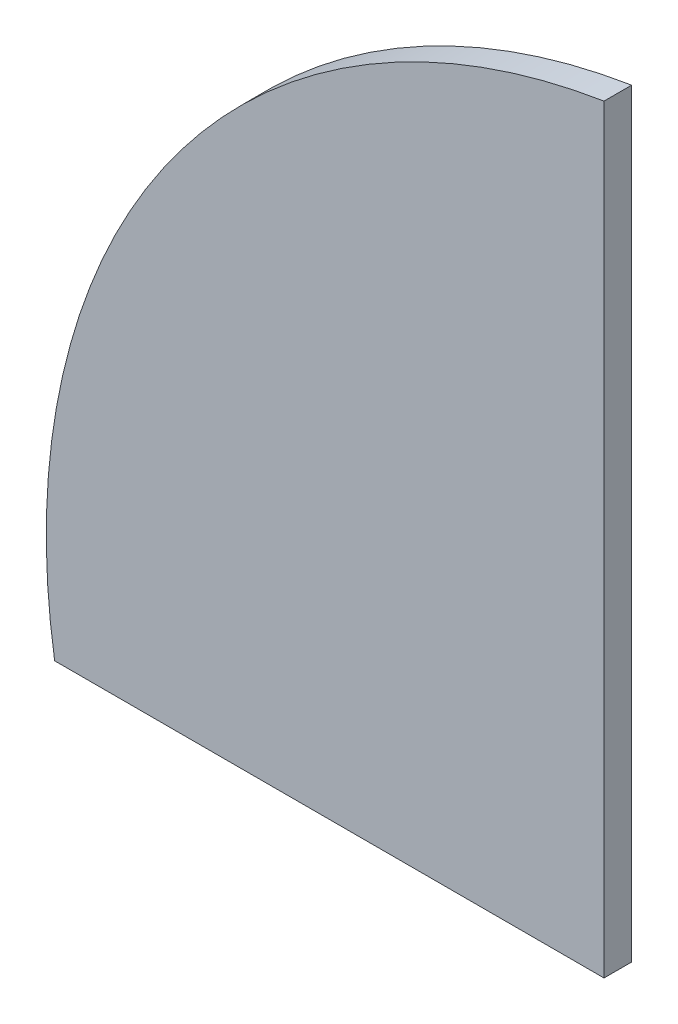
SolidWorks part; units mm, degrees
ref_plane "Front Plane" through (0, 0, 0) normal (0, 0, 1) x (1, 0, 0)
ref_plane "Top Plane" through (0, 0, 0) normal (0, 1, 0) x (1, 0, 0)
ref_plane "Right Plane" through (0, 0, 0) normal (1, 0, 0) x (0, 0, -1)
sketch "Sketch1" plane through (0, 0, 0) normal (0, 0, 1) x (1, 0, 0)
  line L0 (-226.8445, -37.9678) -> (-236.9777, -37.9678) construction
  line L1 (-38.1, -37.9678) -> (-226.8445, -37.9678) construction
  line L2 (-38.1, 236.9565) -> (-38.1, -37.9678) construction
  line L3 (-226.8445, -37.9678) -> (-236.9777, -37.9678)
  line L4 (-38.1, -37.9678) -> (-226.8445, -37.9678)
  line L5 (-38.1, 236.9565) -> (-38.1, -37.9678)
  arc A0 (-38.1, 236.9565) -> (-236.9777, -37.9678) centre (0, 0) ccw construction
  arc A1 (-38.1, 236.9565) -> (-236.9777, -37.9678) centre (0, 0) ccw
extrude "Boss-Extrude1" add sketch "Sketch1" along normal blind 10
